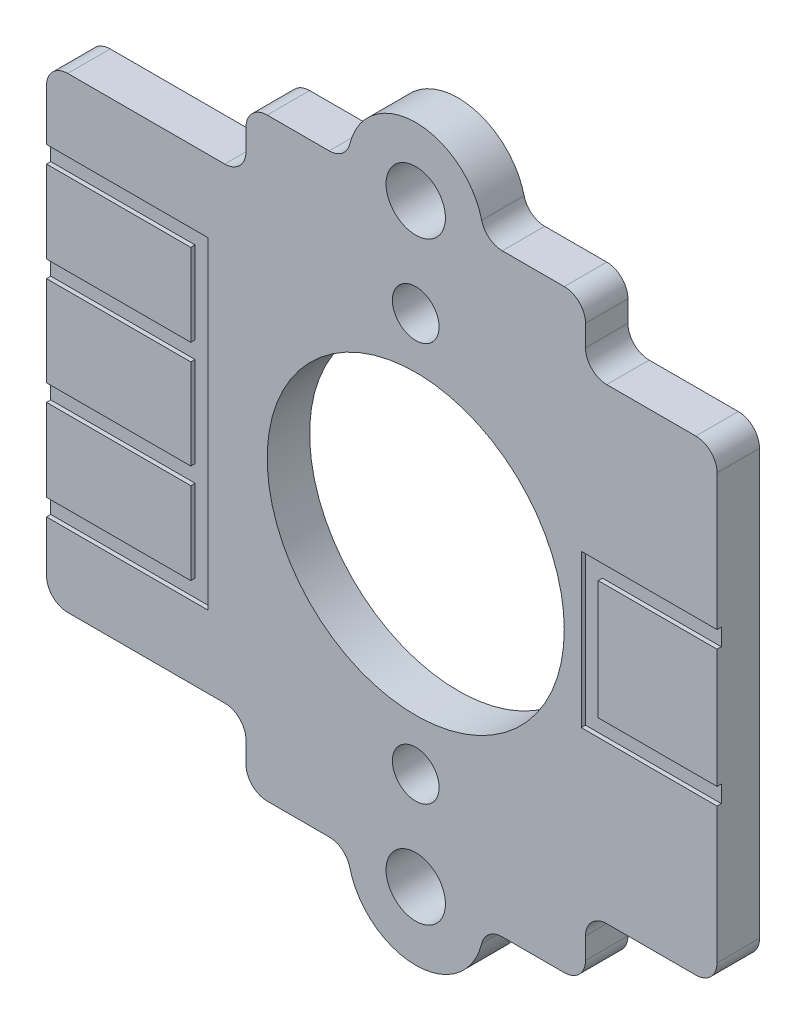
SolidWorks part; units mm, degrees
ref_plane "Спереди" through (0, 0, 0) normal (0, 0, 1) x (1, 0, 0)
ref_plane "Сверху" through (0, 0, 0) normal (0, 1, 0) x (1, 0, 0)
ref_plane "Справа" through (0, 0, 0) normal (1, 0, 0) x (0, 0, -1)
sketch "Model" plane through (0, 0, 0) normal (0, 0, 1) x (1, 0, 0)
  line L0 (-3.5, 7) -> (-2.0396, 7)
  line L2 (-3.5, -7) -> (-2.0396, -7)
  line L4 (-4, 6.5) -> (-4, 6)
  line L6 (4, 6.5) -> (4, 6)
  line L10 (-4, -6) -> (-4, -6.5)
  line L19 (4, -6) -> (4, -6.5)
  line L20 (2.0396, 7) -> (3.5, 7)
  line L24 (2.0396, -7) -> (3.5, -7)
  line L27 (0, 0) -> (0, 6.4277) construction
  line L28 (0, 0) -> (-4.4797, 0) construction
  line L29 (-8.7, 5) -> (-8.7, -5)
  line L30 (7.1, 5) -> (7.1, -5)
  line L31 (-8.2, 5.5) -> (-4.5, 5.5)
  line L32 (-8.2, -5.5) -> (-4.5, -5.5)
  line L36 (4.5, 5.5) -> (6.6, 5.5)
  line L39 (4.5, -5.5) -> (6.6, -5.5)
  arc A28 (-1.554, 7.381) -> (-2.0396, 7) centre (-2.0396, 7.5) cw
  arc A29 (2.0396, 7) -> (1.554, 7.381) centre (2.0396, 7.5) cw
  arc A30 (4.5, -5.5) -> (4, -6) centre (4.5, -6) ccw
  arc A31 (-3.5, 7) -> (-4, 6.5) centre (-3.5, 6.5) ccw
  arc A32 (-4.5, 5.5) -> (-4, 6) centre (-4.5, 6) ccw
  arc A34 (4, 6.5) -> (3.5, 7) centre (3.5, 6.5) ccw
  arc A35 (4.5, 5.5) -> (4, 6) centre (4.5, 6) cw
  circle A36 centre (0, 0) radius 3.5
  arc A37 (-8.2, 5.5) -> (-8.7, 5) centre (-8.2, 5) ccw
  arc A38 (-8.7, -5) -> (-8.2, -5.5) centre (-8.2, -5) ccw
  arc A39 (7.1, -5) -> (6.6, -5.5) centre (6.6, -5) cw
  arc A40 (6.6, 5.5) -> (7.1, 5) centre (6.6, 5) cw
  circle A41 centre (0, 0) radius 7 construction
  arc A42 (1.554, 7.381) -> (-1.554, 7.381) centre (0, 7) ccw
  circle A43 centre (0, 7) radius 0.7
  circle A44 centre (0, -7) radius 0.7
  arc A45 (-1.554, -7.381) -> (1.554, -7.381) centre (0, -7) ccw
  arc A46 (-4, -6) -> (-4.5, -5.5) centre (-4.5, -6) ccw
  arc A47 (-3.5, -7) -> (-4, -6.5) centre (-3.5, -6.5) cw
  arc A48 (-1.554, -7.381) -> (-2.0396, -7) centre (-2.0396, -7.5) ccw
  arc A49 (2.0396, -7) -> (1.554, -7.381) centre (2.0396, -7.5) ccw
  arc A50 (4, -6.5) -> (3.5, -7) centre (3.5, -6.5) cw
  point P13 (1.6, 7)
  point P74 (0, 7)
  point P75 (0, -7)
  dimension "D4" = 14
  dimension "D5" = 0.5
  dimension "D6" = 0.5
  dimension "D10" = 5.5
  dimension "D7" = 8
  dimension "D9" = 5.5
  dimension "D11" = 0.5
  dimension "D18" = 0.5
  dimension "D19" = 0.5
  dimension "D20" = 0.5
  dimension "D26" = 7
  dimension "D29" = 0.5
  dimension "D31" = 0.5
  dimension "D32" = 0.5
  dimension "D33" = 0.5
  dimension "D35" = 3.2
  dimension "D36" = 1.4
  dimension "D37" = 3.2
  dimension "D39" = 1.4
  dimension "D12" = 0.5
  dimension "D13" = 0.5
  dimension "D14" = 0.5
  dimension "D15" = 0.5
  dimension "D16" = 0.5
  dimension "D17" = 0.5
  dimension "D8" = 4
  dimension "D27" = 8.7
  dimension "D28" = 7.1
  dimension "D30" = 5.5
  dimension "D34" = 5.5
extrude "Бобышка-Вытянуть1" add sketch "Model" along normal mid plane 1
sketch "Sketch2" plane through (0, 0, 0.5) normal (0, 0, 1) x (1, 0, 0)
  line L9 (-5.1, 1.4625) -> (-10.1, 1.4625)
  line L18 (-5.1, 0) -> (-5.1, 3.6)
  line L19 (-5.1, 3.6) -> (-10.1, 3.6)
  line L20 (4.1, -1.6) -> (4.1, 1.6)
  line L21 (-5.1, 1.2625) -> (-10.1, 1.2625)
  line L34 (-4.9, 0.2) -> (-4.9, 3.8)
  line L35 (-4.9, 3.8) -> (-10.1, 3.8)
  line L36 (-5.1, 1.0625) -> (-10.1, 1.0625)
  line L38 (4.1, 1.6) -> (8.0158, 1.6)
  line L45 (-5.3, -0.2) -> (-5.3, 3.4)
  line L50 (4.1, -1.6) -> (8.0158, -1.6)
  line L56 (-5.3, 3.4) -> (-10.1, 3.4)
  line L57 (-5.3, 0.2) -> (-5.3, -3.4)
  line L58 (-4.9, -0.2) -> (-4.9, -3.8)
  line L59 (-5.1, 0) -> (-5.1, -3.6)
  line L60 (-5.3, -3.4) -> (-10.1, -3.4)
  line L61 (-5.1, -1.0625) -> (-10.1, -1.0625)
  line L62 (-4.9, -3.8) -> (-10.1, -3.8)
  line L63 (-5.1, -1.2625) -> (-10.1, -1.2625)
  line L64 (-5.1, -3.6) -> (-10.1, -3.6)
  line L65 (-5.1, -1.4625) -> (-10.1, -1.4625)
  line L66 (-9.5574, 5.6022) -> (-9.5574, -4.4906)
  line L67 (4.3, -1.4) -> (8.0158, -1.4)
  line L68 (0, 0) -> (7.1, 0) construction
  line L69 (0, 0.2) -> (7.1, 0.2) construction
  line L70 (0, -0.2) -> (7.1, -0.2) construction
  line L71 (4.3, -1.4) -> (4.3, 1.4)
  line L72 (4.3, 1.4) -> (8.0158, 1.4)
  line L73 (3.9, -1.8) -> (8.0158, -1.8)
  line L74 (3.9, -1.8) -> (3.9, 1.8)
  line L75 (3.9, 1.8) -> (8.0158, 1.8)
  line L76 (7.7397, 2.3128) -> (7.7397, -2.5375)
  line L77 (-4.9, 0.2) -> (-4.9, -0.2)
  line L79 (0, 0) -> (-5.1, 0) construction
  line L80 (0, -0.2) -> (-5.3, -0.2) construction
  line L81 (0, 0.2) -> (-4.9, 0.2) construction
  dimension "D1" = 0.2
  dimension "D2" = 0.2
  dimension "D3" = 3.6
  dimension "D4" = 4.1
  dimension "D5" = 5.1
  dimension "D6" = 3.2
  dimension "D7" = 0.2
  dimension "D8" = 0.2
extrude "Extrude2" cut sketch "Sketch2" against normal blind 0.1
sketch "Sketch3" plane through (0, 0, 0.5) normal (0, 0, 1) x (1, 0, 0)
  circle A0 centre (0, 0) radius 4.7 construction
  circle A1 centre (0, 4.7) radius 0.55
  circle A2 centre (0, -4.7) radius 0.55
extrude "Extrude3" cut sketch "Sketch3" against normal through all
